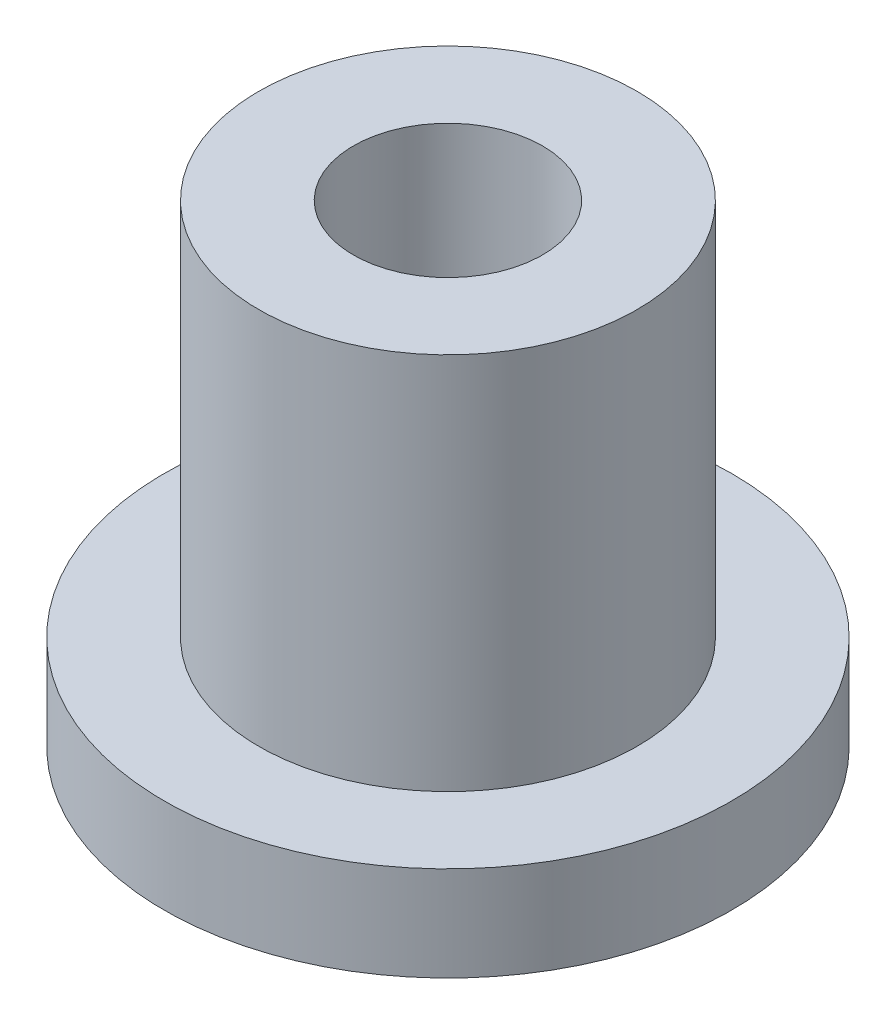
SolidWorks part; units mm, degrees
material "acero"
ref_plane "Alzado" through (0, 0, 0) normal (0, 0, 1) x (1, 0, 0)
ref_plane "Planta" through (0, 0, 0) normal (0, 1, 0) x (1, 0, 0)
ref_plane "Vista lateral" through (0, 0, 0) normal (1, 0, 0) x (0, 0, -1)
sketch "Croquis1" plane through (0, 0, 0) normal (0, 0, 1) x (1, 0, 0)
  line L0 (0, 0) -> (0, 10) construction
  line L1 (-2, 10) -> (-2, 0)
  line L2 (-2, 0) -> (-6, 0)
  line L3 (-6, 0) -> (-6, 2)
  line L4 (-6, 2) -> (-4, 2)
  line L5 (-4, 2) -> (-4, 10)
  line L6 (-4, 10) -> (-2, 10)
  dimension "D1" = 4
  dimension "D2" = 8
  dimension "D3" = 10
  dimension "D4" = 2
  dimension "D5" = 12
revolve "Revolución1" add sketch "Croquis1" angle 360 about L0
